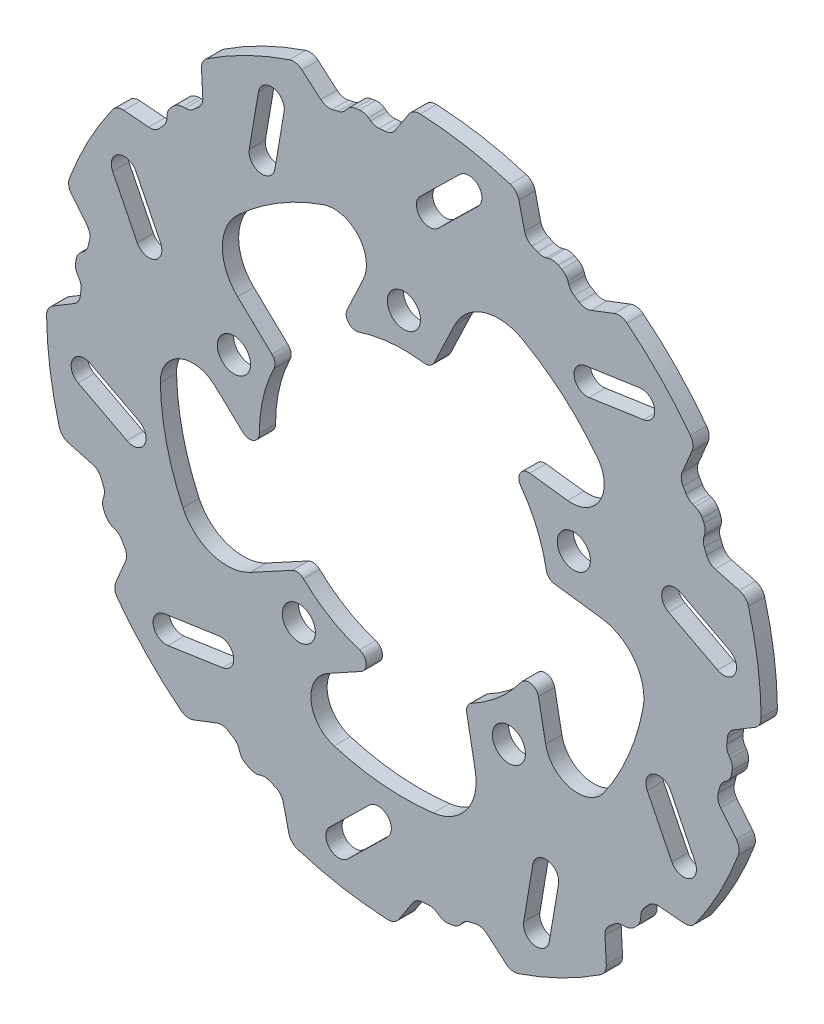
SolidWorks part; units mm, degrees
material "Plain Carbon Steel"
ref_plane "Front Plane" through (0, 0, 0) normal (0, 0, 1) x (1, 0, 0)
ref_plane "Top Plane" through (0, 0, 0) normal (0, 1, 0) x (1, 0, 0)
ref_plane "Right Plane" through (0, 0, 0) normal (1, 0, 0) x (0, 0, -1)
sketch "Sketch1" plane through (0, 0, 0) normal (0, 0, 1) x (1, 0, 0)
  circle A0 centre (0, 0) radius 110
  circle A1 centre (0, 0) radius 44.5
  dimension "D1" = 220
  dimension "D2" = 89
extrude "Extrude1" add sketch "Sketch1" along normal mid plane 5
sketch "Sketch3" plane through (0, 0, 2.5) normal (0, 0, 1) x (1, 0, 0)
  circle A0 centre (0, 55) radius 5.1
  circle A1 centre (52.3081, 16.9959) radius 5.1
  circle A2 centre (32.3282, -44.4959) radius 5.1
  circle A3 centre (-32.3282, -44.4959) radius 5.1
  circle A4 centre (-52.3081, 16.9959) radius 5.1
  circle A5 centre (0, 0) radius 55 construction
  dimension "D1" = 10.2
  dimension "D2" = 110
extrude "Extrude4" cut sketch "Sketch3" against normal through all
sketch "Sketch5" plane through (0, 0, 2.5) normal (0, 0, 1) x (1, 0, 0)
  line L0 (-38.9835, 21.4602) -> (-51.1938, 33.0567)
  line L1 (-20.7993, 39.34) -> (-12.4841, 57.0842)
  arc A0 (-24.8529, 70.7625) -> (-51.0802, 54.9165) centre (0, 0) ccw
  circle A1 centre (0, 0) radius 44.5 construction
  arc A2 (-20.7993, 39.34) -> (-38.9835, 21.4602) centre (0, 0) ccw
  arc A3 (-12.4841, 57.0842) -> (-24.8529, 70.7625) centre (-21.5391, 61.3275) ccw
  arc A4 (-51.1938, 33.0567) -> (-51.0802, 54.9165) centre (-40.8641, 43.9332) cw
  dimension "D1" = 150
  dimension "D2" = 10
  dimension "D3" = 15
extrude "Cut-Extrude2" cut sketch "Sketch5" against normal through all
fillet "Fillet2" radius 3 2 edges at (-38.9835, 21.4602, 0) (-20.7993, 39.34, 0)
pattern_circular "CirPattern1" count 5 over 360 about axis through (0, 0, 0) along (0, 0, 1) of "Cut-Extrude2", "Fillet2"
sketch "Sketch6" plane through (0, 0, 2.5) normal (0, 0, 1) x (1, 0, 0)
  line L0 (-40.8159, 90.232) -> (-43.6545, 73.4707) construction
  line L1 (-36.8721, 89.5641) -> (-39.7107, 72.8028)
  line L2 (-44.7598, 90.8999) -> (-47.5984, 74.1386)
  line L3 (-62.4197, 90.5747) -> (-61.8009, 78.6171)
  line L4 (0, 0) -> (-82.8913, 85.7245) construction
  line L5 (-65.8434, 75.2638) -> (-69.6618, 75.1896)
  line L6 (-88.4266, 65.4274) -> (-76.4965, 64.4072)
  line L7 (-73.0093, 68.3348) -> (-72.8068, 72.1486)
  arc A0 (-36.8721, 89.5641) -> (-44.7598, 90.8999) centre (-40.8159, 90.232) ccw
  arc A1 (-47.5984, 74.1386) -> (-39.7107, 72.8028) centre (-43.6545, 73.4707) ccw
  circle A2 centre (0, 0) radius 110 construction
  arc A3 (-62.4197, 90.5747) -> (-88.4266, 65.4274) centre (0, 0) ccw
  arc A4 (-73.0093, 68.3348) -> (-76.4965, 64.4072) centre (0, 0) ccw
  arc A6 (-69.6618, 75.1896) -> (-72.8068, 72.1486) centre (0, 0) ccw
  arc A7 (-61.8009, 78.6171) -> (-65.8434, 75.2638) centre (0, 0) ccw
  point P2 (-42.2352, 81.8513)
  dimension "D1" = 4
  dimension "D3" = 100
  dimension "D4" = 102.5
  dimension "D2" = 17
extrude "Cut-Extrude3" cut sketch "Sketch6" against normal through all
fillet "Fillet1" radius 4 8 edges at (-62.4197, 90.5747, 0) (-61.8009, 78.6171, 0) (-65.8434, 75.2638, 0) (-69.6618, 75.1896, 0) (-72.8068, 72.1486, 0) (-73.0093, 68.3348, 0) (-76.4965, 64.4072, 0) (-88.4266, 65.4274, 0)
pattern_circular "CirPattern2" count 10 over 360 about axis through (0, 0, 0) along (0, 0, 1) of "Cut-Extrude3", "Fillet1"
